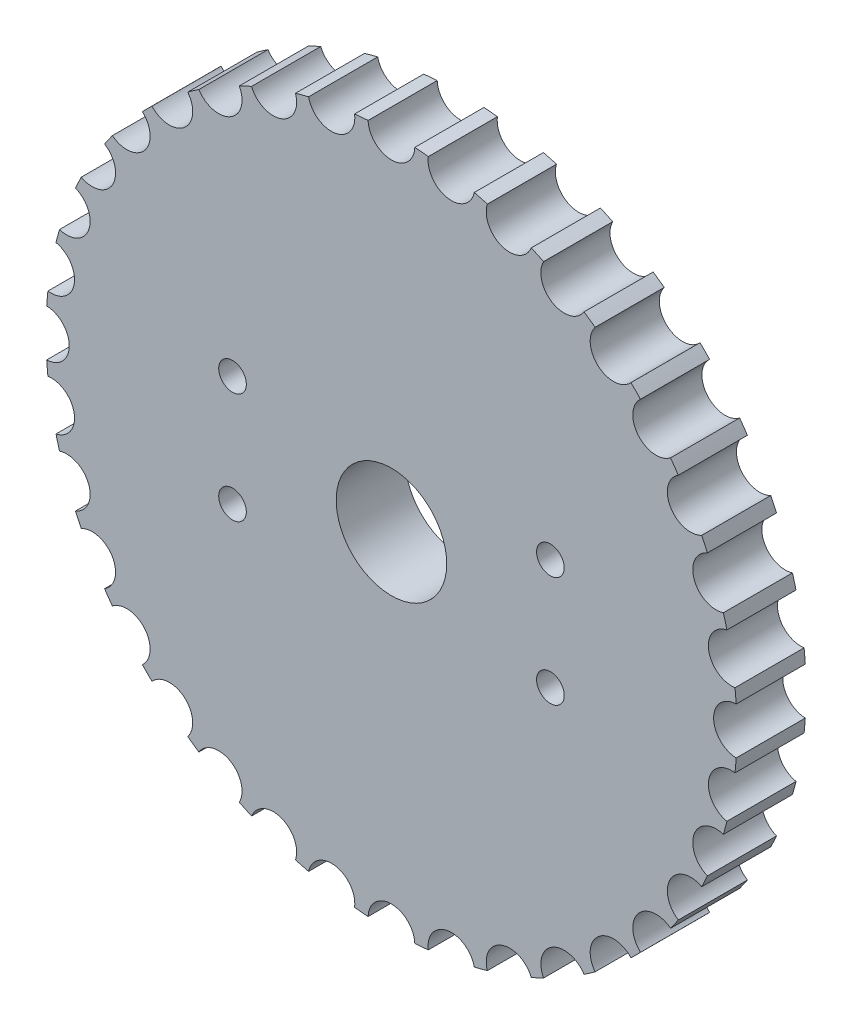
SolidWorks part; units mm, degrees
material "아크릴(내충격성)"
ref_plane "정면" through (0, 0, 0) normal (0, 0, 1) x (1, 0, 0)
ref_plane "윗면" through (0, 0, 0) normal (0, 1, 0) x (1, 0, 0)
ref_plane "우측면" through (0, 0, 0) normal (1, 0, 0) x (0, 0, -1)
sketch "스케치1" plane through (0, 0, 0) normal (0, 0, 1) x (1, 0, 0)
  circle A0 centre (0, 0) radius 50
  dimension "D1" = 100
extrude "보스-돌출1" add sketch "스케치1" along normal blind 10
sketch "스케치2" plane through (0, 0, 10) normal (0, 0, 1) x (1, 0, 0)
  line L0 (0, 0) -> (0, 53.4651) construction
  line L1 (0, 0) -> (9.1386, 52.0133) construction
  line L2 (0, 0) -> (-9.7027, 52.5525) construction
  circle A0 centre (4.373, 49.8084) radius 3.38
  circle A2 centre (0, 0) radius 50 construction
  circle A6 centre (11.6601, 43.4631) radius 3.38
  circle A7 centre (17.7347, 35.9488) radius 3.38
  circle A8 centre (22.4122, 27.4938) radius 3.38
  circle A9 centre (25.5503, 18.3551) radius 3.38
  circle A10 centre (27.0539, 8.8102) radius 3.38
  circle A11 centre (26.8772, -0.8507) radius 3.38
  circle A12 centre (25.0256, -10.3342) radius 3.38
  circle A13 centre (21.5553, -19.3521) radius 3.38
  circle A14 centre (16.5718, -27.6304) radius 3.38
  circle A15 centre (10.2265, -34.9175) radius 3.38
  circle A16 centre (2.7122, -40.9921) radius 3.38
  circle A17 centre (-5.7428, -45.6695) radius 3.38
  circle A18 centre (-14.8815, -48.8077) radius 3.38
  circle A19 centre (-24.4264, -50.3113) radius 3.38
  circle A20 centre (-34.0873, -50.1346) radius 3.38
  circle A21 centre (-43.5708, -48.283) radius 3.38
  circle A22 centre (-52.5887, -44.8127) radius 3.38
  circle A23 centre (-60.867, -39.8292) radius 3.38
  circle A24 centre (-68.1541, -33.4839) radius 3.38
  circle A25 centre (-74.2287, -25.9696) radius 3.38
  circle A26 centre (-78.9061, -17.5146) radius 3.38
  circle A27 centre (-82.0443, -8.3759) radius 3.38
  circle A28 centre (-83.5479, 1.169) radius 3.38
  circle A29 centre (-83.3712, 10.83) radius 3.38
  circle A30 centre (-81.5196, 20.3134) radius 3.38
  circle A31 centre (-78.0493, 29.3313) radius 3.38
  circle A32 centre (-73.0658, 37.6096) radius 3.38
  circle A33 centre (-66.7205, 44.8967) radius 3.38
  circle A34 centre (-59.2062, 50.9713) radius 3.38
  circle A35 centre (-50.7512, 55.6487) radius 3.38
  circle A36 centre (-41.6124, 58.7869) radius 3.38
  circle A37 centre (-32.0676, 60.2905) radius 3.38
  circle A38 centre (-22.4066, 60.1138) radius 3.38
  circle A39 centre (-12.9231, 58.2622) radius 3.38
  circle A40 centre (-3.9053, 54.7919) radius 3.38
  dimension "D1" = 106.9058
  dimension "D2" = 36
sketch "스케치4" plane through (0, 0, 10) normal (0, 0, 1) x (1, 0, 0)
  circle A0 centre (0, 0) radius 8
  dimension "D1" = 16
extrude "컷-돌출3" cut sketch "스케치4" against normal blind 10
sketch "스케치5" plane through (0, 0, 10) normal (0, 0, 1) x (1, 0, 0)
  line L0 (-52.1074, 0) -> (52.2141, 0) construction
  line L1 (-52.1074, -15) -> (52.2141, -15)
  line L2 (-52.1074, 15) -> (52.2141, 15)
  line L3 (0, 53.1222) -> (0, -55.2945) construction
  line L4 (-30, 53.1222) -> (-30, -55.2945)
  line L5 (30, 53.1222) -> (30, -55.2945)
  circle A0 centre (-23, 8) radius 2
  circle A1 centre (23, 8) radius 2
  circle A2 centre (23, -8) radius 2
  circle A3 centre (-23, -8) radius 2
  dimension "D5" = 4
  dimension "D7" = 7
  dimension "D6" = 7
  dimension "D1" = 15
  dimension "D2" = 15
  dimension "D3" = 30
  dimension "D4" = 30
extrude "컷-돌출4" cut sketch "스케치5" against normal blind 10 contours A3 | A0 | A1 | A2
sketch "스케치6" plane through (0, 0, 10) normal (0, 0, 1) x (1, 0, 0)
  line L0 (0, 0) -> (0, 53.4651) construction
  circle A0 centre (0, 50) radius 3.38
  circle A1 centre (0, 0) radius 50 construction
  circle A2 centre (8.6824, 49.2404) radius 3.38
  circle A3 centre (17.101, 46.9846) radius 3.38
  circle A4 centre (25, 43.3013) radius 3.38
  circle A5 centre (32.1394, 38.3022) radius 3.38
  circle A6 centre (38.3022, 32.1394) radius 3.38
  circle A7 centre (43.3013, 25) radius 3.38
  circle A8 centre (46.9846, 17.101) radius 3.38
  circle A9 centre (49.2404, 8.6824) radius 3.38
  circle A10 centre (50, 0) radius 3.38
  circle A11 centre (49.2404, -8.6824) radius 3.38
  circle A12 centre (46.9846, -17.101) radius 3.38
  circle A13 centre (43.3013, -25) radius 3.38
  circle A14 centre (38.3022, -32.1394) radius 3.38
  circle A15 centre (32.1394, -38.3022) radius 3.38
  circle A16 centre (25, -43.3013) radius 3.38
  circle A17 centre (17.101, -46.9846) radius 3.38
  circle A18 centre (8.6824, -49.2404) radius 3.38
  circle A19 centre (0, -50) radius 3.38
  circle A20 centre (-8.6824, -49.2404) radius 3.38
  circle A21 centre (-17.101, -46.9846) radius 3.38
  circle A22 centre (-25, -43.3013) radius 3.38
  circle A23 centre (-32.1394, -38.3022) radius 3.38
  circle A24 centre (-38.3022, -32.1394) radius 3.38
  circle A25 centre (-43.3013, -25) radius 3.38
  circle A26 centre (-46.9846, -17.101) radius 3.38
  circle A27 centre (-49.2404, -8.6824) radius 3.38
  circle A28 centre (-50, 0) radius 3.38
  circle A29 centre (-49.2404, 8.6824) radius 3.38
  circle A30 centre (-46.9846, 17.101) radius 3.38
  circle A31 centre (-43.3013, 25) radius 3.38
  circle A32 centre (-38.3022, 32.1394) radius 3.38
  circle A33 centre (-32.1394, 38.3022) radius 3.38
  circle A34 centre (-25, 43.3013) radius 3.38
  circle A35 centre (-17.101, 46.9846) radius 3.38
  circle A36 centre (-8.6824, 49.2404) radius 3.38
  point P79 (0, 0)
  dimension "D1" = 36
extrude "컷-돌출5" cut sketch "스케치6" against normal through all
